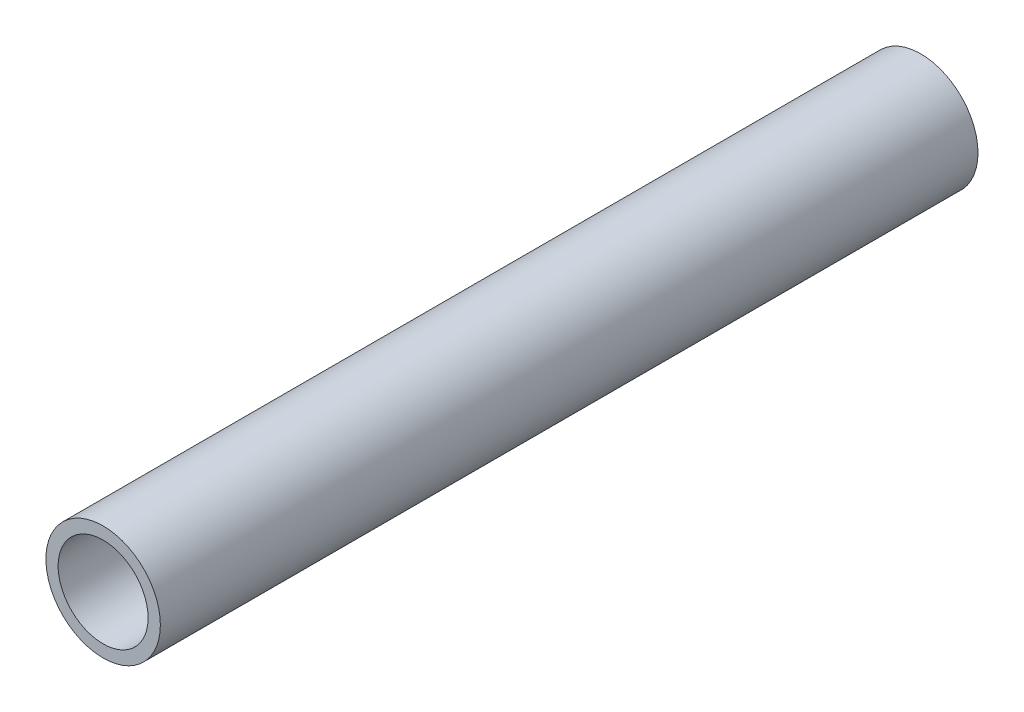
SolidWorks part; units mm, degrees
ref_plane "Front Plane" through (0, 0, 0) normal (0, 0, 1) x (1, 0, 0)
ref_plane "Top Plane" through (0, 0, 0) normal (0, 1, 0) x (1, 0, 0)
ref_plane "Right Plane" through (0, 0, 0) normal (1, 0, 0) x (0, 0, -1)
sketch "Sketch1" plane through (0, 0, 0) normal (0, 0, 1) x (1, 0, 0)
  circle A0 centre (0, 0) radius 2.75
  circle A1 centre (0, 0) radius 3.5
  dimension "D1" = 5.5
  dimension "D2" = 7
extrude "Boss-Extrude1" add sketch "Sketch1" along normal blind 50
